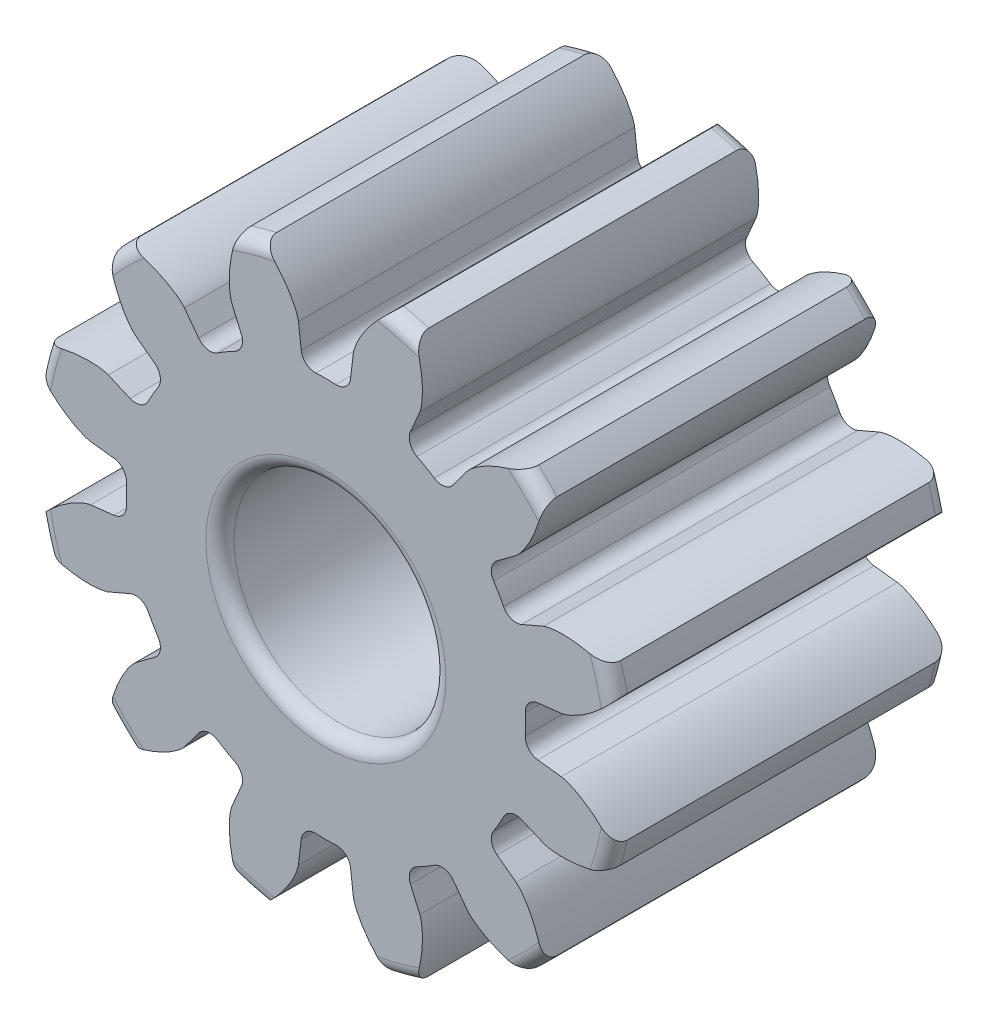
SolidWorks part; units mm, degrees
material "Brass"
ref_plane "Front Plane" through (0, 0, 0) normal (0, 0, 1) x (1, 0, 0)
ref_plane "Top Plane" through (0, 0, 0) normal (0, 1, 0) x (1, 0, 0)
ref_plane "Right Plane" through (0, 0, 0) normal (1, 0, 0) x (0, 0, -1)
sketch "Sketch1" plane through (0, 0, 0) normal (0, 0, 1) x (1, 0, 0)
  line L0 (0, 0) -> (0, 4.7625) construction
  line L1 (-1.5306, 5.3196) -> (1.5306, 4.2054) construction
  circle A0 centre (0, 0) radius 3.7703 construction
  circle A1 centre (0, 0) radius 5.5562 construction
  circle A2 centre (0, 0) radius 4.7625 construction
  circle A3 centre (0, 0) radius 4.4753 construction
  circle A4 centre (0, 0) radius 2.0001 construction
  circle A5 centre (0, 0) radius 3.556 construction
  point P8 (406.4, 0)
  point P13 (152.4, 0)
  dimension "OD | Outside Diameter" = 11.1125
  dimension "Root Diameter" = 7.5406
  dimension "Gear Pitch Diameter" = 9.525
  dimension "Base Diameter" = 8.9506
  dimension "For Shaft Diameter" = 4.0002
  dimension "Hub Diameter" = 7.112
  dimension "Pressure Angle" = 20
  dimension "Number of Teeth" = 304.8
  dimension "Gear Pitch | Diametral Pitch" = 812.8
sketch "Sketch2" plane through (0, 0, 0) normal (1, 0, 0) x (0, 0, -1)
  line L0 (-3.175, 0) -> (3.175, 0) construction
  line L1 (-5.5626, 5.5562) -> (0.7874, 5.5562) construction
  dimension "Overall Width" = 6.35
sketch "Sketch3" plane through (0, 0, 0) normal (0, 0, 1) x (1, 0, 0)
  circle A0 centre (0, 0) radius 5.5562
  circle A1 centre (0, 0) radius 5.5562 construction
extrude "Boss-Extrude1" add sketch "Sketch3" against normal up to vertex (3.175 mm away) and the other way up to vertex (3.175 mm away) up to point (0, 0, -3.175) other way up to point (0, 0, 3.175)
sketch "Sketch5" plane through (0, 0, 0) normal (1, 0, 0) x (0, 0, -1)
  line L11 (3.175, 2.0001) -> (-3.175, 2.0001)
  line L12 (3.175, 2.0001) -> (3.175, 0)
  line L13 (3.175, 0) -> (-3.175, 0)
  line L14 (-3.175, 2.0001) -> (-3.175, 0)
  point P5 (0, 2.0001)
  point P12 (0, 3.556)
revolve "Cut-Revolve1" cut sketch "Sketch5" angle 360 about L0
fillet "Fillet2" radius 0.2663 4 edges at (5.5562, 0, -3.175) (5.5562, 0, 3.175) (2.0001, 0, -3.175) (2.0001, 0, 3.175)
sketch "Sketch4" plane through (0, 0, 0) normal (0, 0, 1) x (1, 0, 0)
  line L0 (0, 0) -> (3.745, 0.4364) construction
  line L2 (0, 0) -> (3.745, -0.4364) construction
  line L4 (3.745, 0.4364) -> (4.4452, 0.5179)
  line L5 (4.4452, -0.5179) -> (3.745, -0.4364)
  arc A0 (3.745, 0.4364) -> (3.745, -0.4364) centre (0, 0) cw
  arc A3 (5.4254, 1.1987) -> (5.4254, -1.1987) centre (0, 0) cw
  circle A4 centre (0, 0) radius 5.5562 construction
  spline S0 degree 4 poles (4.4452, 0.5179) (4.447, 0.5182) (4.452, 0.5189) (4.4613, 0.5207) (4.4765, 0.524) (4.4957, 0.5289) (4.5203, 0.5361) (4.5491, 0.5456) (4.5805, 0.5571) (4.6143, 0.5707) (4.6477, 0.5853) (4.6807, 0.6008) (4.7133, 0.6171) (4.7525, 0.6378) (4.799, 0.6639) (4.8525, 0.6964) (4.9122, 0.7355) (4.9721, 0.7778) (5.03, 0.8214) (5.0874, 0.8676) (5.1422, 0.9139) (5.1978, 0.9642) (5.2486, 1.0117) (5.304, 1.0674) (5.3484, 1.113) (5.4053, 1.1756) (5.4385, 1.2134) (5.4767, 1.2584) (5.4934, 1.2789) (5.5037, 1.2914) knots 0 0 0 0 0 0.005377 0.015084 0.028532 0.04661 0.064855 0.092111 0.119476 0.146842 0.174209 0.201575 0.228941 0.256307 0.307035 0.361767 0.4165 0.471232 0.525964 0.580697 0.635429 0.690161 0.744894 0.799626 0.854358 0.909091 0.954545 1 1 1 1 1 construction
  spline S1 degree 4 poles (4.4452, 0.5179) (4.447, 0.5182) (4.452, 0.5189) (4.4613, 0.5207) (4.4765, 0.524) (4.4957, 0.5289) (4.5203, 0.5361) (4.5491, 0.5456) (4.5805, 0.5571) (4.6143, 0.5707) (4.6477, 0.5853) (4.6807, 0.6008) (4.7133, 0.6171) (4.7525, 0.6378) (4.799, 0.6639) (4.8525, 0.6964) (4.9122, 0.7355) (4.9721, 0.7778) (5.03, 0.8214) (5.0874, 0.8676) (5.1422, 0.9139) (5.1978, 0.9642) (5.2486, 1.0117) (5.304, 1.0674) (5.3484, 1.113) (5.393, 1.1621) (5.4145, 1.1862) (5.4254, 1.1987) knots 0 0 0 0 0 0.005377 0.015084 0.028532 0.04661 0.064855 0.092111 0.119476 0.146842 0.174209 0.201575 0.228941 0.256307 0.307035 0.361767 0.4165 0.471232 0.525964 0.580697 0.635429 0.690161 0.744894 0.799626 0.854358 0.909091 0.909091 0.909091 0.909091 0.909091
  spline S2 degree 4 poles (4.4452, -0.5179) (4.447, -0.5182) (4.452, -0.5189) (4.4613, -0.5207) (4.4765, -0.524) (4.4957, -0.5289) (4.5203, -0.5361) (4.5491, -0.5456) (4.5805, -0.5571) (4.6143, -0.5707) (4.6477, -0.5853) (4.6807, -0.6008) (4.7133, -0.6171) (4.7525, -0.6378) (4.799, -0.6639) (4.8525, -0.6964) (4.9122, -0.7355) (4.9721, -0.7778) (5.03, -0.8214) (5.0874, -0.8676) (5.1422, -0.9139) (5.1978, -0.9642) (5.2486, -1.0117) (5.304, -1.0674) (5.3484, -1.113) (5.4053, -1.1756) (5.4385, -1.2134) (5.4767, -1.2584) (5.4934, -1.2789) (5.5037, -1.2914) knots 0 0 0 0 0 0.005377 0.015084 0.028532 0.04661 0.064855 0.092111 0.119476 0.146842 0.174209 0.201575 0.228941 0.256307 0.307035 0.361767 0.4165 0.471232 0.525964 0.580697 0.635429 0.690161 0.744894 0.799626 0.854358 0.909091 0.954545 1 1 1 1 1 construction
  spline S3 degree 4 poles (4.4452, -0.5179) (4.447, -0.5182) (4.452, -0.5189) (4.4613, -0.5207) (4.4765, -0.524) (4.4957, -0.5289) (4.5203, -0.5361) (4.5491, -0.5456) (4.5805, -0.5571) (4.6143, -0.5707) (4.6477, -0.5853) (4.6807, -0.6008) (4.7133, -0.6171) (4.7525, -0.6378) (4.799, -0.6639) (4.8525, -0.6964) (4.9122, -0.7355) (4.9721, -0.7778) (5.03, -0.8214) (5.0874, -0.8676) (5.1422, -0.9139) (5.1978, -0.9642) (5.2486, -1.0117) (5.304, -1.0674) (5.3484, -1.113) (5.393, -1.1621) (5.4145, -1.1862) (5.4254, -1.1987) knots 0 0 0 0 0 0.005377 0.015084 0.028532 0.04661 0.064855 0.092111 0.119476 0.146842 0.174209 0.201575 0.228941 0.256307 0.307035 0.361767 0.4165 0.471232 0.525964 0.580697 0.635429 0.690161 0.744894 0.799626 0.854358 0.909091 0.909091 0.909091 0.909091 0.909091
  dimension "D1" = 7.5406
extrude "Cut-Extrude1" cut sketch "Sketch4" against normal through all both and the other way through all
fillet "Fillet1" radius 0.2663 2 edges at (3.745, -0.4364, 0) (3.745, 0.4364, 0)
pattern_circular "CirPattern1" count 12 over 360 about axis through (0, 0, 3.175) along (0, 0, -1) of "Cut-Extrude1", "Fillet1"
equation "\"Root Diameter@Sketch1\"=\"Root Diameter\""
equation "\"OD | Outside Diameter@Sketch1\"=\"Outside Diameter\""
equation "\"D1@CirPattern1\"=\"Number of Teeth\""
equation "\"Diametral Pitch\"=32"
equation "\"Number of Teeth\"= 12"
equation "\"Pressure Angle\"=20"
equation "\"Pitch Diameter\"= \"Number of Teeth\" / \"Diametral Pitch\""
equation "\"Base Diameter\"= \"Pitch Diameter\" * cos ( \"Pressure Angle\" )"
equation "\"Outside Diameter\"= ( \"Number of Teeth\" + 2 ) / \"Diametral Pitch\""
equation "\"Dedendum\"= 1.25 / \"Diametral Pitch\""
equation "\"Root Diameter\"= \"Pitch Diameter\" - ( 2 * \"Dedendum\" )"
equation "\"Pitch Angle\"= 360deg / \"Number of Teeth\""
equation "\"Alpha\"= sqr ( \"Pitch Diameter\" ^ 2 - \"Base Diameter\" ^ 2 ) / \"Base Diameter\" * 180 / PI - \"Pressure Angle\""
equation "\"Beta\"= ( \"Pitch Angle\" / 4 - \"Alpha\" )"
equation "\"Phi\"= sqr ( ( \"Outside Diameter\" / 2 ) ^ 2 - ( \"Base Diameter\" / 2 ) ^ 2 ) / ( \"Base Diameter\" / 2 )"
equation "\"Addendum\"= 1 / \"Diametral Pitch\""
equation "\"WorkingDepth\"= 2 / \"Diametral Pitch\""
equation "\"WholeDepth\"= 2.25 / \"Diametral Pitch\""
equation "\"Clearance\"= 0.25 / \"Diametral Pitch\""
equation "\"ToothThickness\"= ( pi * 2 ) / \"Diametral Pitch\""
equation "\"CircularPitch\"= pi / \"Diametral Pitch\""
equation "\"Number of Teeth@Sketch1\"=\"Number of Teeth\""
equation "\"Gear Pitch | Diametral Pitch@Sketch1\"=\"Diametral Pitch\""
equation "\"Pressure Angle@Sketch1\"=\"Pressure Angle\""
equation "\"Gear Pitch Diameter@Sketch1\"=\"Pitch Diameter\""
equation "\"Base Diameter@Sketch1\"=\"Base Diameter\""
equation "\"Fillet\"= \"Clearance\" * cos ( \"Pressure Angle\" ) * tan ( ( 90 + \"Pressure Angle\" ) / 2 )"
equation "\"D1@Fillet1\"=\"Fillet\""
equation "\"D1@Sketch4\"=if( \"Base Diameter\">\"Root Diameter\",\"Root Diameter\",\"Base Diameter\"-.00001)"
equation "\"D1@Fillet2\"=\"Fillet\""
